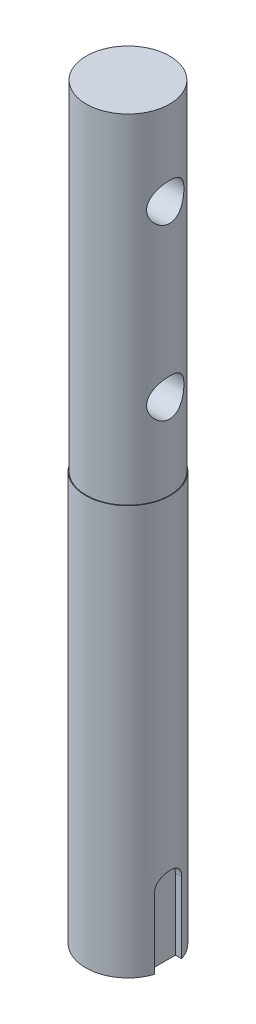
SolidWorks part; units mm, degrees
material "ASTM A36 Steel"
ref_plane "Front Plane" through (0, 0, 0) normal (0, 0, 1) x (1, 0, 0)
ref_plane "Top Plane" through (0, 0, 0) normal (0, 1, 0) x (1, 0, 0)
ref_plane "Right Plane" through (0, 0, 0) normal (1, 0, 0) x (0, 0, -1)
sketch "Sketch1" plane through (0, 0, 0) normal (0, 1, 0) x (1, 0, 0)
  circle A0 centre (0, 0) radius 25
  dimension "D1" = 50
extrude "Boss-Extrude1" add sketch "Sketch1" along normal blind 241.5
sketch "Sketch2" plane through (0, 241.5, 0) normal (0, 1, 0) x (1, 0, 0)
  circle A0 centre (0, 0) radius 24.61
  dimension "D1" = 49.22
extrude "Boss-Extrude2" add sketch "Sketch2" along normal blind 200
ref_plane "Plane1" through (25, 0, 0) normal (1, 0, 0) x (0, 0, -1)
sketch "Sketch3" plane through (25, 0, 0) normal (1, 0, 0) x (0, 0, -1)
  line L0 (-25, 0) -> (25, 0) construction
  line L1 (-8, 42) -> (-8, 0)
  line L2 (-8, 0) -> (8, 0)
  line L3 (8, 0) -> (8, 42)
  arc A0 (8, 42) -> (-8, 42) centre (0, 42) ccw
  dimension "D1" = 16
  dimension "D2" = 42
extrude "Cut-Extrude1" cut sketch "Sketch3" against normal blind 5
sketch "Sketch4" plane through (0, 0, 0) normal (1, 0, 0) x (0, 0, -1)
  line L0 (25, 241.5) -> (-25, 241.5) construction
  circle A0 centre (0, 291.5) radius 11
  circle A1 centre (0, 391.5) radius 11
  dimension "D1" = 22
  dimension "D2" = 22
  dimension "D3" = 50
  dimension "D4" = 100
extrude "Cut-Extrude2" cut sketch "Sketch4" against normal through all both and the other way through all
